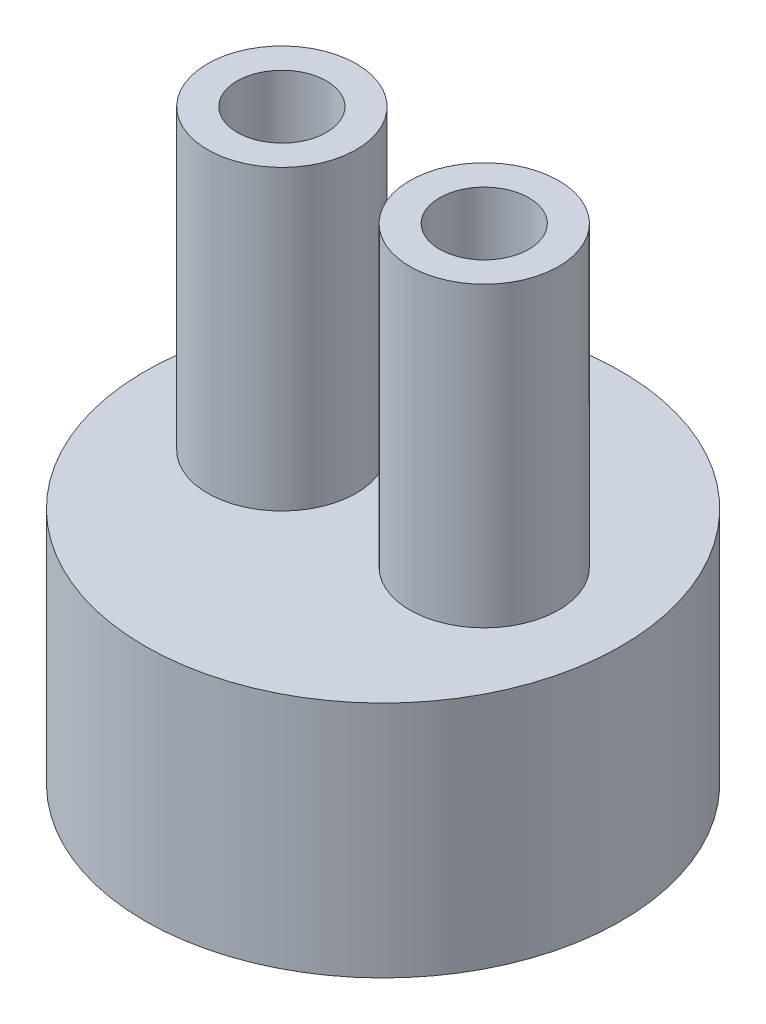
SolidWorks part; units mm, degrees
material "AISI 1020"
ref_plane "Front Plane" through (0, 0, 0) normal (0, 0, 1) x (1, 0, 0)
ref_plane "Top Plane" through (0, 0, 0) normal (0, 1, 0) x (1, 0, 0)
ref_plane "Right Plane" through (0, 0, 0) normal (1, 0, 0) x (0, 0, -1)
ref_plane "Plane1" through (0, 7.62, 0) normal (0, 1, 0) x (1, 0, 0)
sketch "Sketch4" plane through (0, 0, 0) normal (1, 0, 0) x (0, 0, -1)
  line L0 (0, 0) -> (-3.3921, 0)
  line L1 (-3.3921, 0) -> (-10.16, 2.4633)
  line L2 (-10.16, 2.4633) -> (-10.16, 10.0833)
  line L3 (-10.16, 10.0833) -> (0, 10.0833)
  line L4 (0, 10.0833) -> (0, 0)
  dimension "D1" = 20
  dimension "D2" = 10.16
  dimension "D3" = 7.62
  dimension "D4" = 10.0833
revolve "Revolve1" add sketch "Sketch4" angle 360 about L4
shell "Shell1" thickness 2.54
sketch "Sketch5" plane through (0, 10.0833, 0) normal (0, 1, 0) x (1, 0, 0)
  line L0 (-10.16, 0) -> (10.16, 0) construction
  circle A0 centre (0, 0) radius 10.16 construction
  circle A1 centre (-4.318, 0) radius 1.905
  circle A2 centre (4.318, 0) radius 1.905
  circle A3 centre (-4.318, 0) radius 3.175
  circle A4 centre (4.318, 0) radius 3.175
  dimension "D1" = 3.81
  dimension "D4" = 4.318
  dimension "D5" = 4.318
  dimension "D2" = 1.27
  dimension "D3" = 1.27
extrude "Boss-Extrude1" add sketch "Sketch5" along normal blind 15.24
sketch "Sketch6" plane through (0, 0, 0) normal (0, -1, 0) x (1, 0, 0)
  circle A1 centre (0, 0) radius 3.3921
  circle A2 centre (0, 0) radius 3.3921
  dimension "D1" = 0
extrude "Cut-Extrude1" cut sketch "Sketch6" against normal up to next
sketch "Sketch7" plane through (0, 10.0833, 0) normal (0, 1, 0) x (1, 0, 0)
  circle A0 centre (-4.318, 0) radius 3.175 construction
  circle A1 centre (0, 0) radius 10.16
  circle A2 centre (0, 0) radius 10.16
  circle A3 centre (4.318, 0) radius 3.175 construction
  circle A4 centre (-4.318, 0) radius 3.175
  circle A5 centre (4.318, 0) radius 3.175
  dimension "D1" = 0
extrude "Boss-Extrude2" add sketch "Sketch7" along normal blind 2.54
